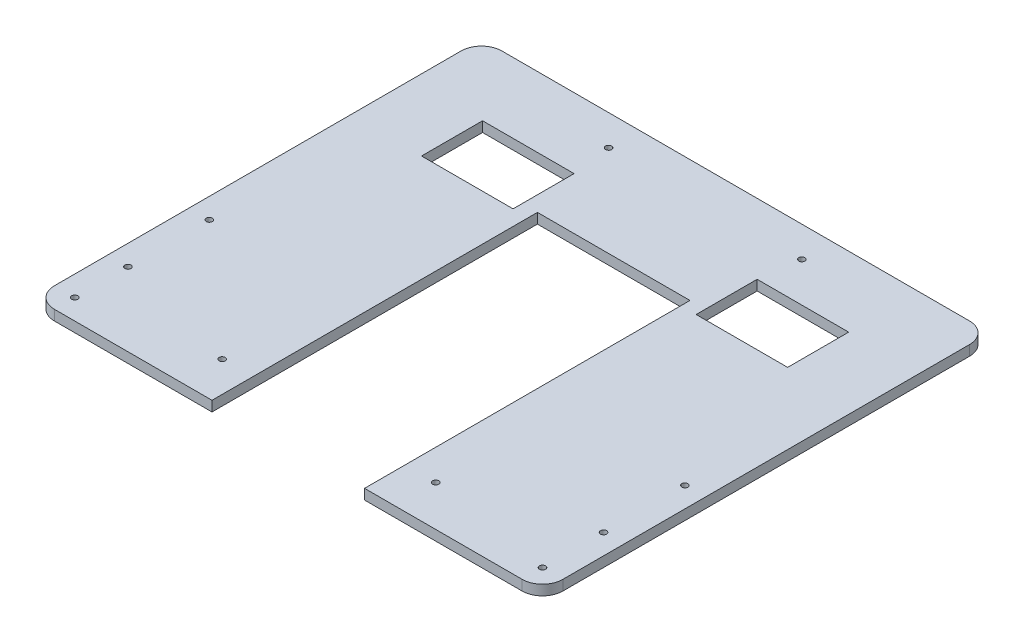
SolidWorks part; units mm, degrees
ref_plane "前视基准面" through (0, 0, 0) normal (0, 0, 1) x (1, 0, 0)
ref_plane "上视基准面" through (0, 0, 0) normal (0, 1, 0) x (1, 0, 0)
ref_plane "右视基准面" through (0, 0, 0) normal (1, 0, 0) x (0, 0, -1)
sketch "草图1" plane through (0, 0, 0) normal (0, 1, 0) x (1, 0, 0)
  line L1 (10, 0) -> (240, 0)
  line L2 (0, -10) -> (0, -210)
  line L3 (10, -220) -> (240, -220)
  line L4 (250, -10) -> (250, -210)
  arc A0 (0, -210) -> (10, -220) centre (10, -210) ccw
  arc A1 (240, -220) -> (250, -210) centre (240, -210) ccw
  arc A2 (240, 0) -> (250, -10) centre (240, -10) cw
  arc A3 (10, 0) -> (0, -10) centre (10, -10) ccw
  point P9 (250, -220)
  point P12 (250, 0)
  point P15 (0, 0)
  dimension "D3" = 10
  dimension "D1" = 250
  dimension "D2" = 220
extrude "凸台-拉伸1" add sketch "草图1" along normal blind 5
sketch "草图2" plane through (0, 0, 0) normal (0, -1, 0) x (1, 0, 0)
  line L0 (239.1778, 11.85) -> (239.1778, 76.15) construction
  line L1 (239.1778, 11.85) -> (239.1778, 76.15)
  line L2 (250, 210) -> (250, 10) construction
  line L3 (239.1778, 76.15) -> (250, 76.15)
  line L4 (239.1778, 76.15) -> (239.1778, 0)
  line L5 (239.1778, 0) -> (250, 0)
  line L6 (250, 76.15) -> (250, 0)
  line L7 (125, 220) -> (125, 0) construction
  line L8 (10, 220) -> (240, 220) construction
  line L9 (240, 0) -> (10, 0) construction
  line L10 (0, 76.15) -> (0, 0)
  line L11 (10.8222, 0) -> (0, 0)
  line L12 (10.8222, 76.15) -> (10.8222, 0)
  line L13 (10.8222, 76.15) -> (0, 76.15)
sketch "草图4" plane through (0, 0, 0) normal (0, -1, 0) x (1, 0, 0)
  line L1 (125, 0) -> (125, 220) construction
  line L2 (240, 0) -> (10, 0) construction
  line L3 (10, 220) -> (240, 220) construction
  line L8 (170, 64.475) -> (170, 34.475)
  line L16 (215, 34.475) -> (170, 34.475)
  line L17 (215, 64.475) -> (215, 34.475)
  line L18 (215, 64.475) -> (170, 64.475)
  line L19 (209.9, 64.475) -> (215, 64.475)
  line L20 (215, 64.475) -> (215, 46.825)
  line L21 (204.1, 64.475) -> (199, 64.475)
  line L22 (209.9, 64.475) -> (215, 64.475)
  line L23 (204.1, 64.475) -> (199, 64.475)
  line L24 (40.1, 64.475) -> (45.9, 64.475)
  line L25 (35, 64.475) -> (35, 46.825)
  line L26 (45.9, 64.475) -> (51, 64.475)
  line L27 (215, 64.475) -> (215, 46.825)
  line L28 (209.9, 64.475) -> (204.1, 64.475)
  line L29 (0, 10) -> (0, 210) construction
  line L30 (40.1, 64.475) -> (35, 64.475)
  line L31 (45.9, 64.475) -> (51, 64.475)
  line L33 (35, 64.475) -> (35, 46.825)
  line L35 (40.1, 64.475) -> (35, 64.475)
  line L38 (35, 64.475) -> (80, 64.475)
  line L39 (35, 64.475) -> (35, 34.475)
  line L120 (35, 34.475) -> (80, 34.475)
  line L121 (80, 64.475) -> (80, 34.475)
  dimension "D3" = 45
  dimension "D4" = 30
  dimension "D1" = 35
extrude "切除-拉伸3" cut sketch "草图4" against normal blind 5
sketch "草图5" plane through (0, 0, 0) normal (0, -1, 0) x (1, 0, 0)
  line L0 (125, 220) -> (125, 0) construction
  line L1 (10, 220) -> (240, 220) construction
  line L2 (240, 0) -> (10, 0) construction
  line L3 (87.5, 220) -> (162.5, 220) construction
  line L4 (87.5, 220) -> (87.5, 60)
  line L5 (162.5, 220) -> (87.5, 220)
  line L6 (162.5, 220) -> (162.5, 60)
  line L7 (162.5, 60) -> (87.5, 60)
  point P11 (125, 60)
  dimension "D1" = 37.5
  dimension "D2" = 160
extrude "切除-拉伸4" cut sketch "草图5" against normal blind 5
sketch "草图6" plane through (0, 0, 0) normal (0, -1, 0) x (1, 0, 0)
  line L0 (72.5, 220) -> (72.5, 200) construction
  line L1 (10, 220) -> (87.5, 220) construction
  line L2 (72.5, 200) -> (87.5, 200) construction
  line L7 (87.5, 220) -> (87.5, 60) construction
  line L8 (125, 60) -> (125, 181.8158) construction
  line L9 (87.5, 60) -> (162.5, 60) construction
  line L10 (87.5, 60) -> (87.5, 0) construction
  line L11 (240, 0) -> (10, 0) construction
  line L12 (87.5, 20) -> (92.5, 20) construction
  line L13 (92.5, 20) -> (92.5, 0) construction
  line L14 (92.5, 20) -> (107.5, 20) construction
  circle A0 centre (72.5, 200) radius 1.5
  circle A3 centre (177.5, 200) radius 1.5
  dimension "D3" = 3
  dimension "D1" = 20
  dimension "D2" = 15
  dimension "D4" = 5
  dimension "D5" = 20
  dimension "D6" = 15
extrude "切除-拉伸5" cut sketch "草图6" against normal up to next
sketch "草图7" plane through (0, 0, 0) normal (0, -1, 0) x (1, 0, 0)
  line L0 (17, 15) -> (17, 73) construction
  line L1 (25, 29) -> (25, 59) construction
  line L2 (17, 44) -> (25, 44) construction
  line L3 (240, 0) -> (10, 0) construction
  line L5 (125, 60) -> (125, 0) construction
  line L6 (87.5, 60) -> (162.5, 60) construction
  line L8 (233, 44) -> (225, 44) construction
  line L9 (225, 29) -> (225, 59) construction
  line L10 (233, 15) -> (233, 73) construction
  line L11 (0, 10) -> (0, 210) construction
  circle A0 centre (17, 15) radius 1.6
  circle A1 centre (25, 29) radius 1.6
  circle A2 centre (25, 59) radius 1.6
  circle A3 centre (17, 73) radius 1.6
  circle A4 centre (233, 73) radius 1.6
  circle A5 centre (225, 59) radius 1.6
  circle A6 centre (225, 29) radius 1.6
  circle A7 centre (233, 15) radius 1.6
  dimension "D1" = 8
  dimension "D2" = 58
  dimension "D3" = 30
  dimension "D4" = 58
  dimension "D5" = 17
  dimension "D6" = 15
sketch "草图8" plane through (0, 0, 0) normal (0, -1, 0) x (1, 0, 0)
  line L0 (250, 170) -> (235, 170) construction
  line L1 (250, 210) -> (250, 10) construction
  line L2 (235, 170) -> (235, 220) construction
  line L3 (162.5, 220) -> (240, 220) construction
  line L4 (235, 170) -> (235, 100) construction
  line L5 (235, 100) -> (250, 100) construction
  line L6 (125, 60) -> (125, 122.441) construction
  line L7 (87.5, 60) -> (162.5, 60) construction
  line L8 (15, 170) -> (15, 100) construction
  circle A0 centre (235, 170) radius 1.5
  circle A1 centre (235, 100) radius 1.5
  circle A2 centre (15, 100) radius 1.5
  circle A3 centre (15, 170) radius 1.5
  dimension "D4" = 3
  dimension "D5" = 3
  dimension "D1" = 15
  dimension "D2" = 50
  dimension "D3" = 70
sketch "草图9" plane through (0, 0, 0) normal (0, -1, 0) x (1, 0, 0)
  line L0 (87.5, 60) -> (87.5, 0) construction
  line L1 (240, 0) -> (10, 0) construction
  line L2 (87.5, 0) -> (87.5, 15) construction
  line L3 (87.5, 15) -> (77.5, 15) construction
  line L4 (10, 220) -> (10, 210) construction
  line L5 (125, 60) -> (125, 0) construction
  line L6 (87.5, 60) -> (162.5, 60) construction
  circle A0 centre (77.5, 15) radius 1.5
  circle A1 centre (10, 210) radius 1.5
  circle A2 centre (240, 210) radius 1.5
  circle A3 centre (172.5, 15) radius 1.5
  dimension "D3" = 3
  dimension "D4" = 3
  dimension "D1" = 15
  dimension "D2" = 10
extrude "切除-拉伸9" cut sketch "草图9" against normal up to next
sketch "草图10" plane through (0, 0, 0) normal (0, -1, 0) x (1, 0, 0)
  line L0 (125, 60) -> (125, 0) construction
  line L1 (0, 0) -> (8, 0)
  line L2 (0, 0) -> (0, 85)
  line L3 (0, 85) -> (8, 85)
  line L4 (8, 0) -> (8, 85)
  line L5 (87.5, 60) -> (162.5, 60) construction
  line L6 (240, 0) -> (10, 0) construction
  line L7 (242, 0) -> (242, 85)
  line L8 (250, 85) -> (242, 85)
  line L9 (250, 0) -> (250, 85)
  line L10 (250, 0) -> (242, 0)
  dimension "D1" = 8
  dimension "D2" = 85
sketch "草图11" plane through (0, 0, 0) normal (0, -1, 0) x (1, 0, 0)
  circle A0 centre (240, 180) radius 1.5 construction
  circle A1 centre (240, 180) radius 1.5
  circle A2 centre (240, 140) radius 1.5 construction
  circle A3 centre (240, 140) radius 1.5
  circle A4 centre (10, 143.8355) radius 1.5 construction
  circle A5 centre (10, 143.8355) radius 1.5
  circle A6 centre (10, 183.8355) radius 1.5 construction
  circle A7 centre (10, 183.8355) radius 1.5
extrude "切除-拉伸10" cut sketch "草图11" against normal up to surface (5 mm away) up to face at (172.5, 5, 16.5)
